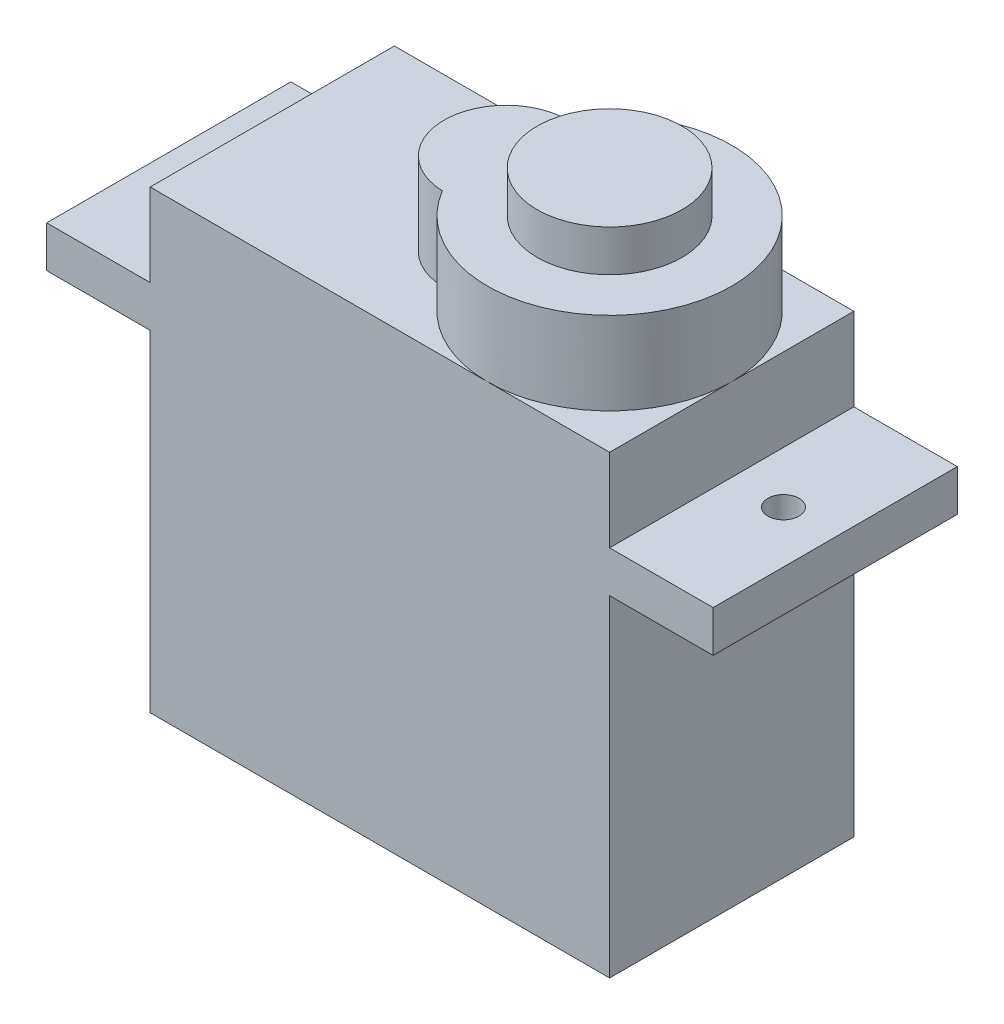
SolidWorks part; units mm, degrees
ref_plane "Front Plane" through (0, 0, 0) normal (0, 0, 1) x (1, 0, 0)
ref_plane "Top Plane" through (0, 0, 0) normal (0, 1, 0) x (1, 0, 0)
ref_plane "Right Plane" through (0, 0, 0) normal (1, 0, 0) x (0, 0, -1)
sketch "Sketch1" plane through (0, 0, 0) normal (0, 1, 0) x (1, 0, 0)
  line L1 (11.1, -5.9) -> (-11.1, -5.9)
  line L2 (11.1, -5.9) -> (11.1, 5.9)
  line L3 (11.1, 5.9) -> (-11.1, 5.9)
  line L4 (-11.1, -5.9) -> (-11.1, 5.9)
  line L5 (11.1, -5.9) -> (-11.1, 5.9) construction
  line L6 (11.1, 5.9) -> (-11.1, -5.9) construction
  point P0 (0, 0)
  dimension "D1" = 11.8
  dimension "D2" = 22.2
extrude "Boss-Extrude1" add sketch "Sketch1" against normal blind 22 contours L2 L1 L4 L3
sketch "Sketch2" plane through (0, 0, 5.9) normal (0, 0, 1) x (1, 0, 0)
  line L0 (0, 0) -> (0, -22) construction
  line L1 (11.1, -22) -> (-11.1, -22) construction
  line L2 (11.1, -6) -> (11.1, -4)
  line L3 (11.1, -6) -> (16.1, -6)
  line L4 (11.1, -4) -> (16.1, -4)
  line L5 (16.1, -6) -> (16.1, -4)
  line L6 (11.1, -22) -> (11.1, 0) construction
  line L7 (-11.1, -6) -> (-11.1, -4)
  line L8 (-16.1, -6) -> (-16.1, -4)
  line L9 (-11.1, -4) -> (-16.1, -4)
  line L10 (-11.1, -6) -> (-16.1, -6)
  dimension "D1" = 2
  dimension "D2" = 16
  dimension "D3" = 16.1
extrude "Boss-Extrude2" add sketch "Sketch2" against normal blind 11.8
sketch "Sketch3" plane through (0, 0, 0) normal (0, 1, 0) x (1, 0, 0)
  point P0 (0, 0)
sketch "Sketch4" plane through (0, 0, 0) normal (0, 1, 0) x (1, 0, 0)
  line L0 (-16.1, 0) -> (16.1, 0) construction
  line L1 (-16.1, 5.9) -> (-16.1, -5.9) construction
  line L2 (16.1, 5.9) -> (16.1, -5.9) construction
  line L3 (11.1, 5.9) -> (11.1, -5.9) construction
  arc A3 (0.119, -2.9989) -> (0.119, 2.9989) centre (5.2, 0) ccw
  arc A4 (0.119, 2.9989) -> (0.119, -2.9989) centre (0.2, 0) ccw
  dimension "D1" = 11.8
  dimension "D2" = 5.9
  dimension "D3" = 3
  dimension "D4" = 5
extrude "Boss-Extrude3" add sketch "Sketch4" along normal blind 4 contours A3 A4
sketch "Sketch5" plane through (0, 4, 0) normal (0, 1, 0) x (1, 0, 0)
  circle A0 centre (5.2, 0) radius 3.5
  dimension "D1" = 7
extrude "Boss-Extrude5" add sketch "Sketch5" along normal blind 2
sketch "Sketch6" plane through (0, -4, 0) normal (0, 1, 0) x (1, 0, 0)
  line L0 (11.1, 0) -> (16.1, 0) construction
  line L1 (16.1, 5.9) -> (16.1, -5.9) construction
  line L2 (0, 0) -> (0, 5.9) construction
  line L3 (5.2, 5.9) -> (-11.1, 5.9) construction
  arc A0 (0.119, -2.9989) -> (0.119, 2.9989) centre (5.2, 0) ccw construction
  circle A1 centre (13.6, 0) radius 0.75
  circle A2 centre (-13.6, 0) radius 0.75
  dimension "D1" = 1.5
extrude "Cut-Extrude2" cut sketch "Sketch6" against normal blind 2 contours A2 | A1
